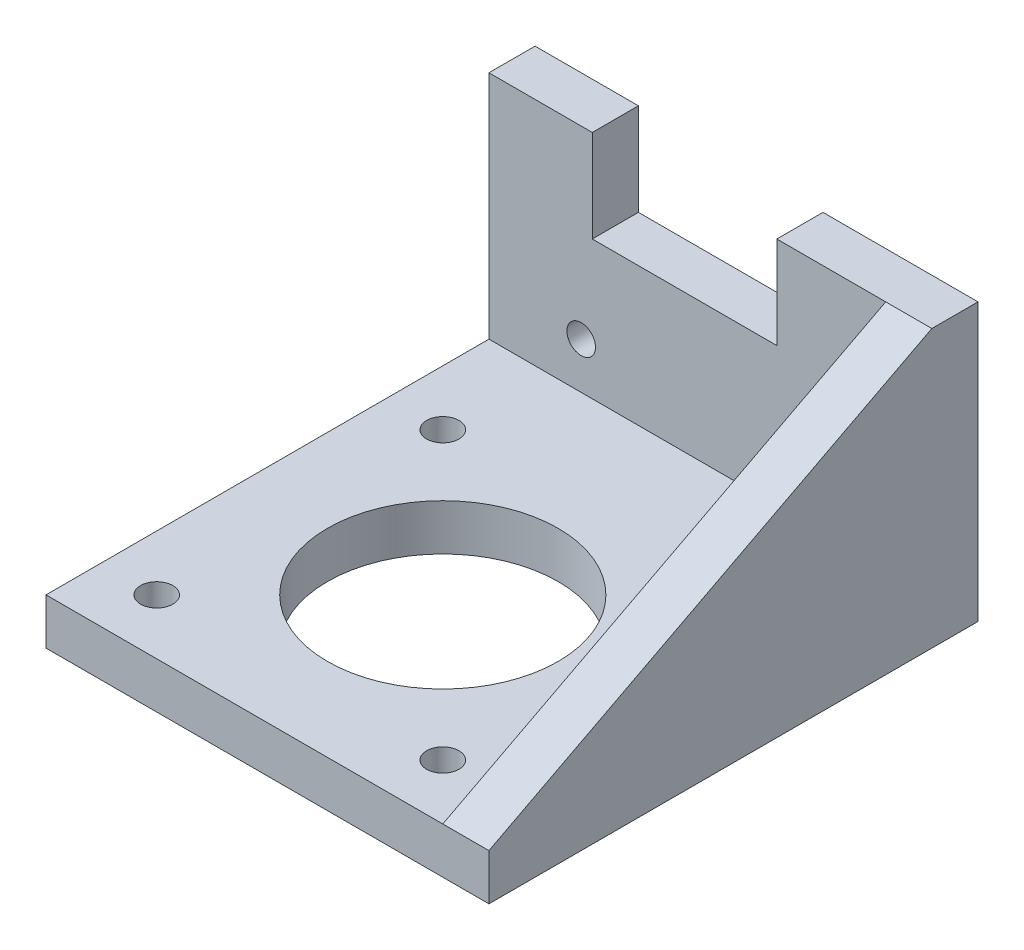
SolidWorks part; units mm, degrees
ref_plane "前视基准面" through (0, 0, 0) normal (0, 0, 1) x (1, 0, 0)
ref_plane "上视基准面" through (0, 0, 0) normal (0, 1, 0) x (1, 0, 0)
ref_plane "右视基准面" through (0, 0, 0) normal (1, 0, 0) x (0, 0, -1)
sketch "草图1" plane through (0, 0, 0) normal (0, 1, 0) x (1, 0, 0)
  line L1 (-35.8997, 33.2122) -> (7.1003, 33.2122)
  line L2 (-35.8997, 33.2122) -> (-35.8997, -9.7878)
  line L3 (-35.8997, -9.7878) -> (7.1003, -9.7878)
  line L4 (7.1003, 33.2122) -> (7.1003, -9.7878)
  line L5 (-14.3997, -9.7878) -> (-14.3997, 33.2122) construction
  line L6 (-35.8997, 11.7122) -> (7.1003, 11.7122) construction
  line L7 (-29.8997, 27.2122) -> (1.1003, 27.2122) construction
  line L8 (-29.8997, 27.2122) -> (-29.8997, -3.7878) construction
  line L9 (-29.8997, -3.7878) -> (1.1003, -3.7878) construction
  line L10 (1.1003, 27.2122) -> (1.1003, -3.7878) construction
  line L11 (-14.3997, -3.7878) -> (-14.3997, 27.2122) construction
  line L12 (-29.8997, 11.7122) -> (1.1003, 11.7122) construction
  circle A0 centre (1.1003, 27.2122) radius 1.75
  circle A1 centre (-29.8997, 27.2122) radius 1.75
  circle A2 centre (-29.8997, -3.7878) radius 1.75
  circle A3 centre (1.1003, -3.7878) radius 1.75
  circle A4 centre (-14.3997, 11.7122) radius 12.5
  point P0 (-14.3997, 11.7122)
  point P4 (-14.3997, 11.7122)
  dimension "D4" = 3.5
  dimension "D5" = 25
  dimension "D1" = 43
  dimension "D2" = 43
  dimension "D3" = 31
extrude "凸台-拉伸1" add sketch "草图1" along normal blind 5
sketch "草图3" plane through (0, 0, -33.2122) normal (0, 0, -1) x (-1, 0, 0)
  line L4 (-7.1003, 0) -> (35.8997, 0)
  line L5 (35.8997, 0) -> (35.8997, 5)
  line L6 (35.8997, 5) -> (-7.1003, 5)
  line L7 (-7.1003, 5) -> (-7.1003, 0)
  line L8 (-7.1003, 0) -> (35.8997, 0)
  line L9 (35.8997, 0) -> (35.8997, 5)
  line L10 (35.8997, 5) -> (-7.1003, 5)
  line L11 (-7.1003, 5) -> (-7.1003, 0)
  dimension "D1" = 0
extrude "凸台-拉伸2" add sketch "草图3" along normal blind 5
sketch "草图4" plane through (0, 0, -38.2122) normal (0, 0, -1) x (-1, 0, 0)
  line L1 (35.8997, 0) -> (-7.1003, 0)
  line L2 (35.8997, 0) -> (35.8997, 30)
  line L3 (35.8997, 30) -> (-7.1003, 30)
  line L4 (-7.1003, 0) -> (-7.1003, 30)
  line L5 (35.8997, 0) -> (-7.1003, 30) construction
  line L6 (35.8997, 30) -> (-7.1003, 0) construction
  point P4 (14.3997, 15)
  dimension "D1" = 30
extrude "凸台-拉伸3" add sketch "草图4" along normal blind 5
sketch "草图5" plane through (0, 0, -38.2122) normal (0, 0, 1) x (1, 0, 0)
  line L0 (7.8515, -92.7386) -> (7.8515, -99.9386) construction
  line L1 (170.7789, -92.7386) -> (142.7446, -92.7386) construction
  line L2 (170.7789, -99.9386) -> (142.7446, -99.9386) construction
  line L3 (7.1003, 10) -> (-35.8997, 10) construction
  line L4 (7.1003, 30) -> (7.1003, 5) construction
  line L5 (-35.8997, 5) -> (-35.8997, 30) construction
  circle A0 centre (-0.8997, 10) radius 1.55
  circle A1 centre (-25.8997, 10) radius 1.55
  dimension "D1" = 3.1
  dimension "D2" = 3.1
  dimension "D3" = 25
  dimension "D4" = 8
extrude "切除-拉伸1" cut sketch "草图5" against normal through all
sketch "草图6" plane through (7.1003, 0, 0) normal (1, 0, 0) x (0, 0, -1)
  line L1 (-9.7878, 0) -> (-9.7878, 5)
  line L2 (-9.7878, 5) -> (38.2122, 30)
  line L3 (38.2122, 30) -> (43.2122, 30)
  line L4 (43.2122, 30) -> (43.2122, 0)
  line L5 (43.2122, 0) -> (-9.7878, 0)
extrude "凸台-拉伸4" add sketch "草图6" along normal blind 5
sketch "草图7" plane through (0, 30, 0) normal (0, 1, 0) x (1, 0, 0)
  line L0 (-4.6997, 38.2122) -> (-4.6997, 43.2122)
  line L1 (-35.8997, 38.2122) -> (7.1003, 38.2122) construction
  line L2 (-35.8997, 43.2122) -> (12.1003, 43.2122) construction
  line L3 (-4.6997, 43.2122) -> (-24.6997, 43.2122)
  line L4 (-24.6997, 43.2122) -> (-24.6997, 38.2122)
  line L5 (-24.6997, 38.2122) -> (-4.6997, 38.2122)
  line L6 (-35.8997, 43.2122) -> (-35.8997, 38.2122) construction
  dimension "D1" = 20
  dimension "D2" = 11.2
extrude "切除-拉伸2" cut sketch "草图7" against normal blind 10
